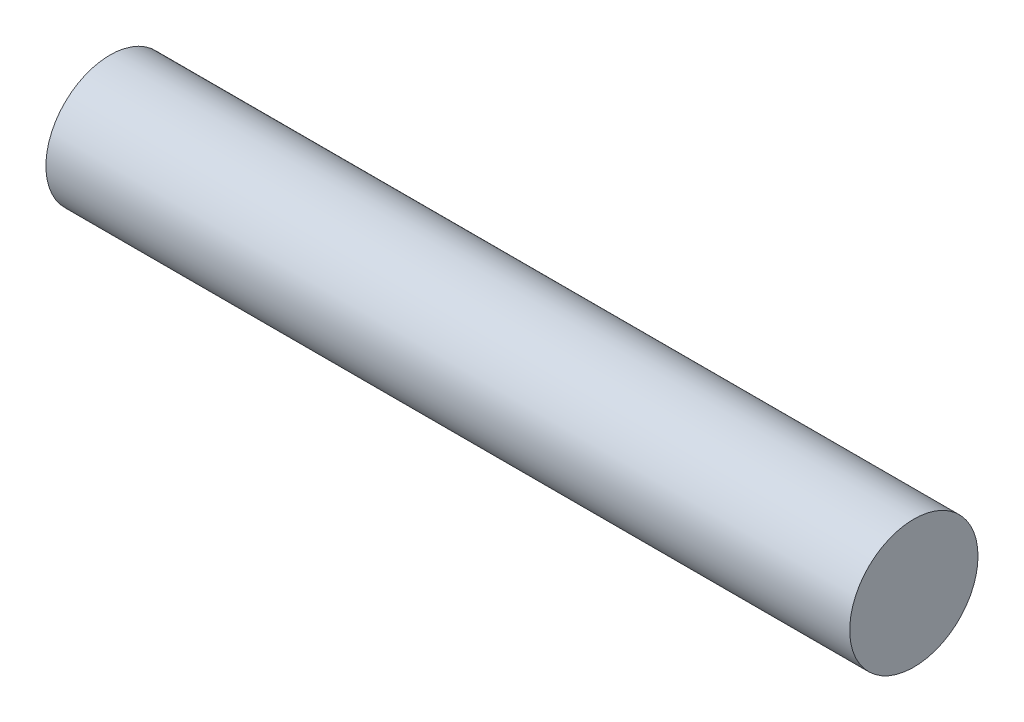
SolidWorks part; units mm, degrees
ref_plane "Front Plane" through (0, 0, 0) normal (0, 0, 1) x (1, 0, 0)
ref_plane "Top Plane" through (0, 0, 0) normal (0, 1, 0) x (1, 0, 0)
ref_plane "Right Plane" through (0, 0, 0) normal (1, 0, 0) x (0, 0, -1)
sketch "Sketch1" plane through (0, 0, 0) normal (1, 0, 0) x (0, 0, -1)
  circle A0 centre (0, 0) radius 1.995
  dimension "D1" = 3.99
extrude "Boss-Extrude1" add sketch "Sketch1" along normal blind 25
